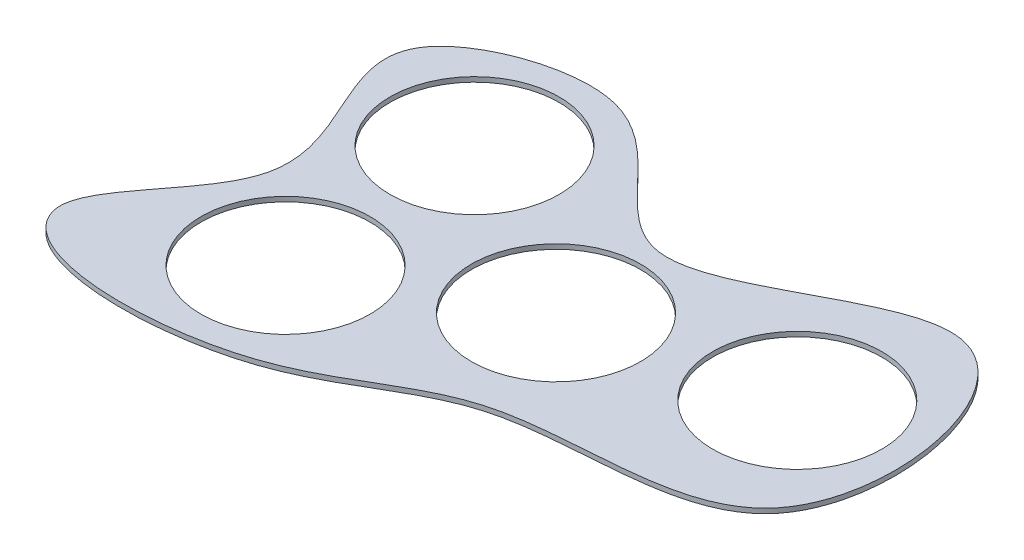
SolidWorks part; units mm, degrees
ref_plane "Front Plane" through (0, 0, 0) normal (0, 0, 1) x (1, 0, 0)
ref_plane "Top Plane" through (0, 0, 0) normal (0, 1, 0) x (1, 0, 0)
ref_plane "Right Plane" through (0, 0, 0) normal (1, 0, 0) x (0, 0, -1)
sketch "Sketch1" plane through (0, 0, 0) normal (0, 1, 0) x (1, 0, 0)
  line L1 (0, 0) -> (431.8, 0) construction
  line L2 (0, 0) -> (0, 330.2) construction
  line L3 (0, 330.2) -> (431.8, 330.2) construction
  line L4 (431.8, 0) -> (431.8, 330.2) construction
  circle A0 centre (102.4861, 227.9587) radius 55.88
  circle A1 centre (225.0363, 159.2277) radius 55.88
  circle A2 centre (108.5376, 97.0398) radius 55.88
  circle A3 centre (354.8326, 188.8361) radius 55.88
  spline S0 degree 3 poles (10.9143, 15.8725) (-6.6933, 75.4554) (99.4878, 156.7471) (-29.0456, 261.5735) (153.7295, 329.9726) (209.8062, 169.2525) (409.0162, 359.1806) (462.6413, 68.1598) (250.7151, 106.0797) (163.7667, 15.8408) (10.9143, 15.8725) (-6.6933, 75.4554) (99.4878, 156.7471) knots -0.22937 -0.132885 -0.013289 0 0.081741 0.2 0.274551 0.379128 0.494919 0.643465 0.77063 0.867115 0.986711 1 1.081741 1.2 1.274551 only from (0, 56.6445) to (0, 56.6445)
  dimension "D3" = 111.76
  dimension "D1" = 330.2
  dimension "D2" = 431.8
extrude "Boss-Extrude1" add sketch "Sketch1" along normal blind 3.175
